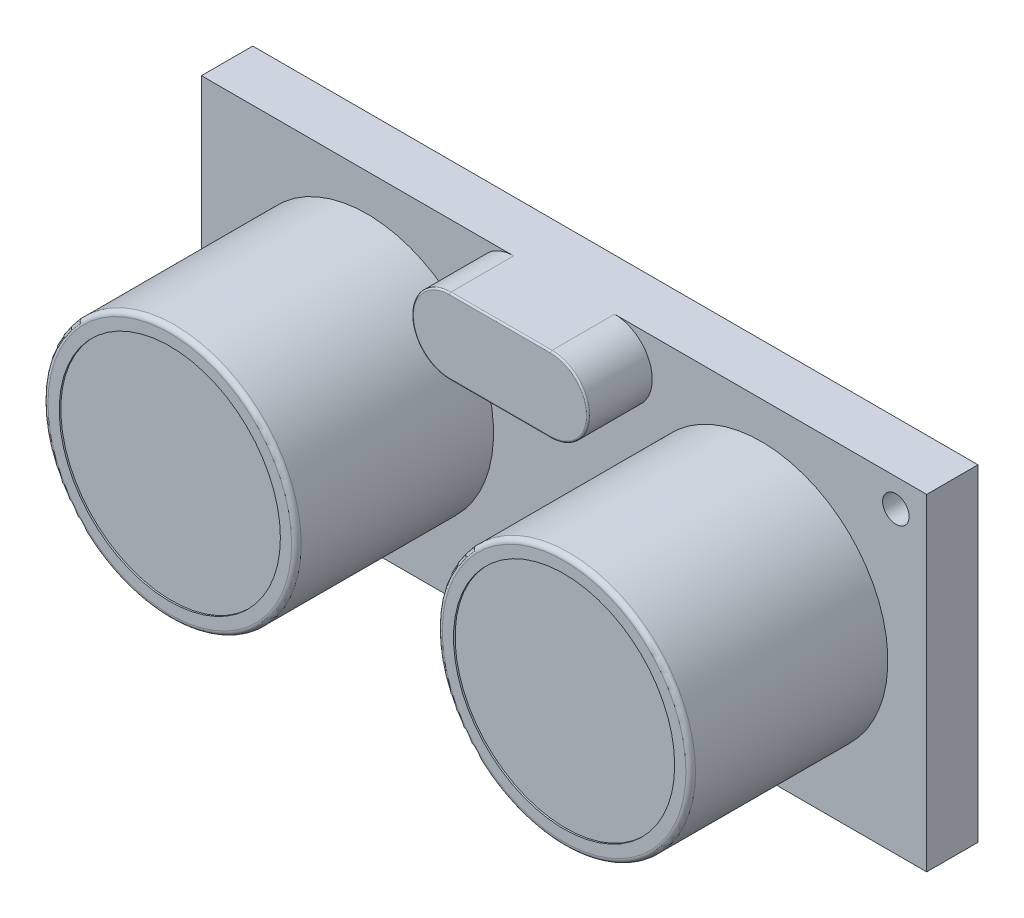
SolidWorks part; units mm, degrees
ref_plane "Front" through (0, 0, 0) normal (0, 0, 1) x (1, 0, 0)
ref_plane "Top" through (0, 0, 0) normal (0, 1, 0) x (1, 0, 0)
ref_plane "Right" through (0, 0, 0) normal (1, 0, 0) x (0, 0, -1)
sketch "Эскиз1" plane through (0, 0, 0) normal (0, 0, 1) x (1, 0, 0)
  line L1 (-22.625, -10.2) -> (22.625, -10.2)
  line L2 (-22.625, -10.2) -> (-22.625, 10.2)
  line L3 (-22.625, 10.2) -> (22.625, 10.2)
  line L4 (22.625, -10.2) -> (22.625, 10.2)
  line L5 (-22.625, -10.2) -> (22.625, 10.2) construction
  line L6 (-22.625, 10.2) -> (22.625, -10.2) construction
  point P0 (0, 0)
  dimension "D1" = 45.25
  dimension "D2" = 20.4
extrude "Бобышка-Вытянуть1" add sketch "Эскиз1" along normal blind 3.2
sketch "Эскиз2" plane through (0, 0, 3.2) normal (0, 0, 1) x (1, 0, 0)
  line L0 (-3.15, 7.85) -> (3.15, 7.85) construction
  line L1 (-3.15, 10.2) -> (3.15, 10.2)
  line L2 (-3.15, 5.5) -> (3.15, 5.5)
  line L3 (22.625, 10.2) -> (-22.625, 10.2) construction
  line L4 (0, 7.85) -> (0, 10.2) construction
  arc A0 (-3.15, 10.2) -> (-3.15, 5.5) centre (-3.15, 7.85) ccw
  arc A1 (3.15, 5.5) -> (3.15, 10.2) centre (3.15, 7.85) ccw
  point P2 (0, 7.85)
  dimension "D1" = 2.35
  dimension "D2" = 6.3
extrude "Бобышка-Вытянуть2" add sketch "Эскиз2" along normal blind 4
fillet "Скругление1" radius 0.1 4 edges at (0, 10.2, 7.2) (5.5, 7.85, 7.2) (0, 5.5, 7.2) (-5.5, 7.85, 7.2)
sketch "Эскиз3" plane through (0, 0, 3.2) normal (0, 0, 1) x (1, 0, 0)
  line L0 (-12.3, 0) -> (12.3, 0) construction
  circle A0 centre (-12.3, 0) radius 7.9
  circle A1 centre (12.3, 0) radius 7.9
  dimension "D2" = 15.8
  dimension "D3" = 24.6
extrude "Бобышка-Вытянуть3" add sketch "Эскиз3" along normal blind 12.3
sketch "Эскиз4" plane through (0, 0, 15.5) normal (0, 0, 1) x (1, 0, 0)
  circle A0 centre (-12.3, 0) radius 6.9
  circle A1 centre (12.3, 0) radius 6.9
  circle A2 centre (-12.3, 0) radius 7.9 construction
  circle A3 centre (12.3, 0) radius 7.9 construction
  dimension "D1" = 1
  dimension "D2" = 1
extrude "Вырез-Вытянуть1" cut sketch "Эскиз4" against normal blind 0.1
fillet "Скругление2" radius 0.3 2 edges at (20.2, 0, 15.5) (-4.4, 0, 15.5)
sketch "Эскиз5" plane through (0, 0, 3.2) normal (0, 0, 1) x (1, 0, 0)
  line L1 (-5.3025, -7.8599) -> (5.3025, -7.8599)
  line L2 (-5.3025, -7.8599) -> (-5.3025, -8.6107)
  line L3 (-5.3025, -8.6107) -> (5.3025, -8.6107)
  line L4 (5.3025, -7.8599) -> (5.3025, -8.6107)
  line L5 (-5.3025, -7.8599) -> (5.3025, -8.6107) construction
  line L6 (-5.3025, -8.6107) -> (5.3025, -7.8599) construction
  point P0 (0, -8.2353)
extrude "Бобышка-Вытянуть4" add sketch "Эскиз5" along normal blind 1
sketch "Эскиз6" plane through (0, 0, 0) normal (0, 0, -1) x (-1, 0, 0)
  line L1 (-5.15, -7.7) -> (5.15, -7.7)
  line L2 (-5.15, -7.7) -> (-5.15, -10.2)
  line L3 (-5.15, -10.2) -> (5.15, -10.2)
  line L4 (5.15, -7.7) -> (5.15, -10.2)
  line L5 (-5.15, -7.7) -> (5.15, -10.2) construction
  line L6 (-5.15, -10.2) -> (5.15, -7.7) construction
  line L7 (22.625, -10.2) -> (-22.625, -10.2) construction
  point P0 (0, -8.95)
  dimension "D1" = 2.5
  dimension "D2" = 10.3
extrude "Бобышка-Вытянуть5" add sketch "Эскиз6" along normal blind 4.5 separate body
sketch "Эскиз7" plane through (0, -10.2, 0) normal (0, -1, 0) x (1, 0, 0)
  circle A0 centre (-3.8948, -3.5331) radius 0.6009
  circle A1 centre (-1.3948, -3.5331) radius 0.6009
  circle A2 centre (1.1052, -3.5331) radius 0.6009
  circle A3 centre (3.6052, -3.5331) radius 0.6009
  dimension "D1" = 4
extrude "Бобышка-Вытянуть6" add sketch "Эскиз7" along normal blind 8
sketch "Эскиз8" plane through (0, 0, 0) normal (0, 0, -1) x (-1, 0, 0)
  line L0 (-21.525, 8.45) -> (-21.525, 9.275) construction
  line L1 (-22.625, -10.2) -> (-22.625, 10.2) construction
  line L2 (-20.7, 9.275) -> (-17.499, 9.275) construction
  line L4 (0, 0) -> (0, 3.2463) construction
  line L5 (20.7, 9.275) -> (17.499, 9.275) construction
  line L7 (-22.625, 0) -> (-14.0289, 0) construction
  line L8 (22.075, -8.75) -> (22.075, -9.575) construction
  line L9 (20.7, -9.275) -> (17.499, -9.275) construction
  line L10 (-20.7, -9.275) -> (-17.499, -9.275) construction
  line L11 (-21.525, -8.45) -> (-21.525, -9.275) construction
  line L12 (20.7, 8.45) -> (-20.7, 8.45) construction
  line L13 (0, 0) -> (0, 8.45) construction
  circle A0 centre (-20.7, 8.45) radius 0.825
  circle A2 centre (20.7, -8.45) radius 0.825
  dimension "D1" = 1.65
  dimension "D3" = 16.9
  dimension "D2" = 41.4
extrude "Вырез-Вытянуть2" cut sketch "Эскиз8" against normal blind 10
